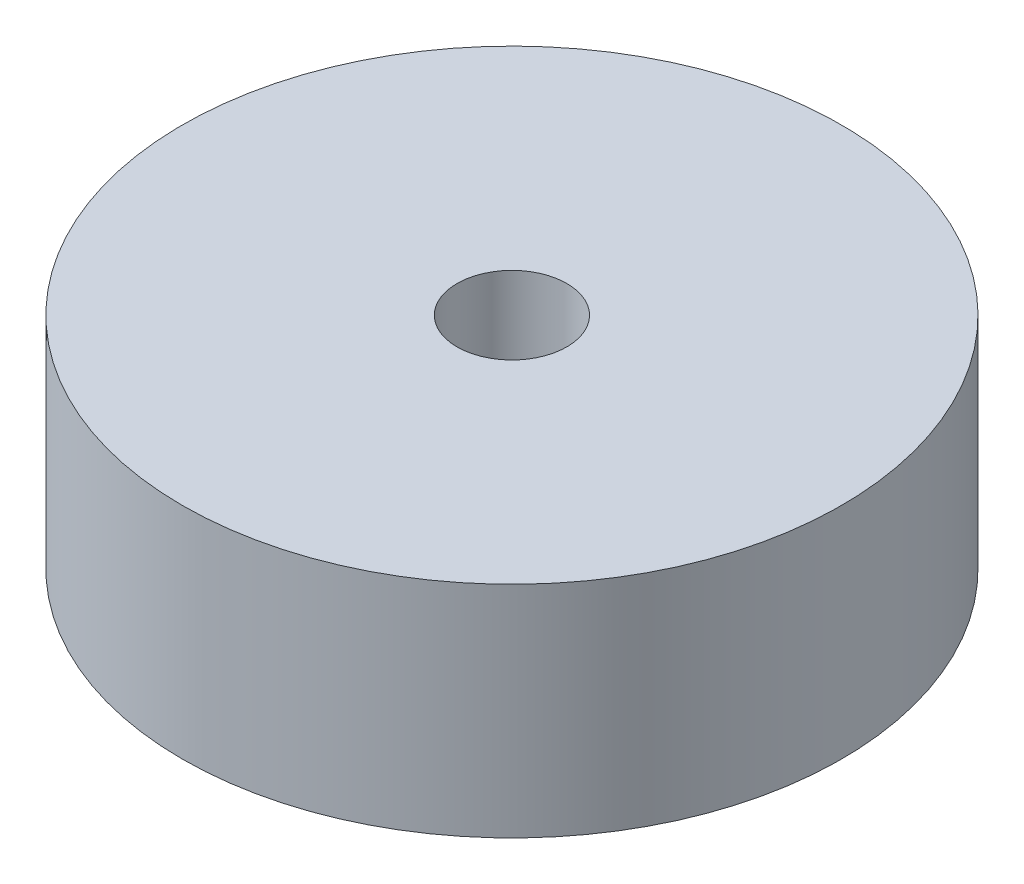
SolidWorks part; units mm, degrees
material "6061 Alloy"
ref_plane "Front Plane" through (0, 0, 0) normal (0, 0, 1) x (1, 0, 0)
ref_plane "Top Plane" through (0, 0, 0) normal (0, 1, 0) x (1, 0, 0)
ref_plane "Right Plane" through (0, 0, 0) normal (1, 0, 0) x (0, 0, -1)
sketch "Sketch1" plane through (0, 0, 0) normal (0, 1, 0) x (1, 0, 0)
  circle A0 centre (0, 0) radius 19.05
  dimension "D1" = 38.1
extrude "Boss-Extrude1" add sketch "Sketch1" along normal blind 12.7
sketch "Sketch2" plane through (0, 12.7, 0) normal (0, 1, 0) x (1, 0, 0)
  circle A0 centre (0, 0) radius 3.175
  dimension "D1" = 6.35
extrude "Cut-Extrude1" cut sketch "Sketch2" against normal blind 12.7
